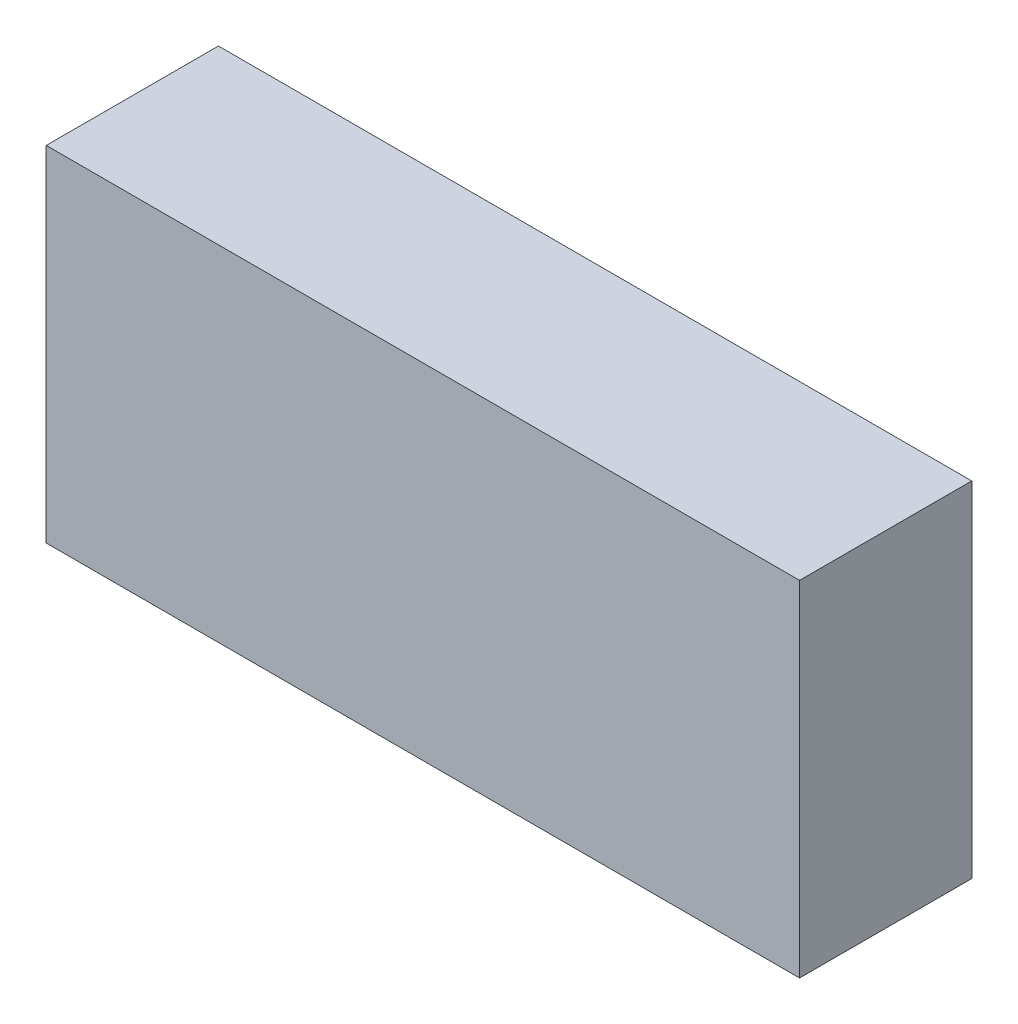
SolidWorks part; units mm, degrees
ref_plane "Alzado" through (0, 0, 0) normal (0, 0, 1) x (1, 0, 0)
ref_plane "Planta" through (0, 0, 0) normal (0, 1, 0) x (1, 0, 0)
ref_plane "Vista lateral" through (0, 0, 0) normal (1, 0, 0) x (0, 0, -1)
sketch "Croquis1" plane through (0, 0, 0) normal (0, 1, 0) x (1, 0, 0)
  line L1 (17.5, -4) -> (-17.5, -4)
  line L2 (17.5, -4) -> (17.5, 4)
  line L3 (17.5, 4) -> (-17.5, 4)
  line L4 (-17.5, -4) -> (-17.5, 4)
  line L5 (17.5, -4) -> (-17.5, 4) construction
  line L6 (17.5, 4) -> (-17.5, -4) construction
  point P0 (0, 0)
  dimension "D1" = 35
  dimension "D2" = 8
extrude "Saliente-Extruir1" add sketch "Croquis1" along normal blind 16
